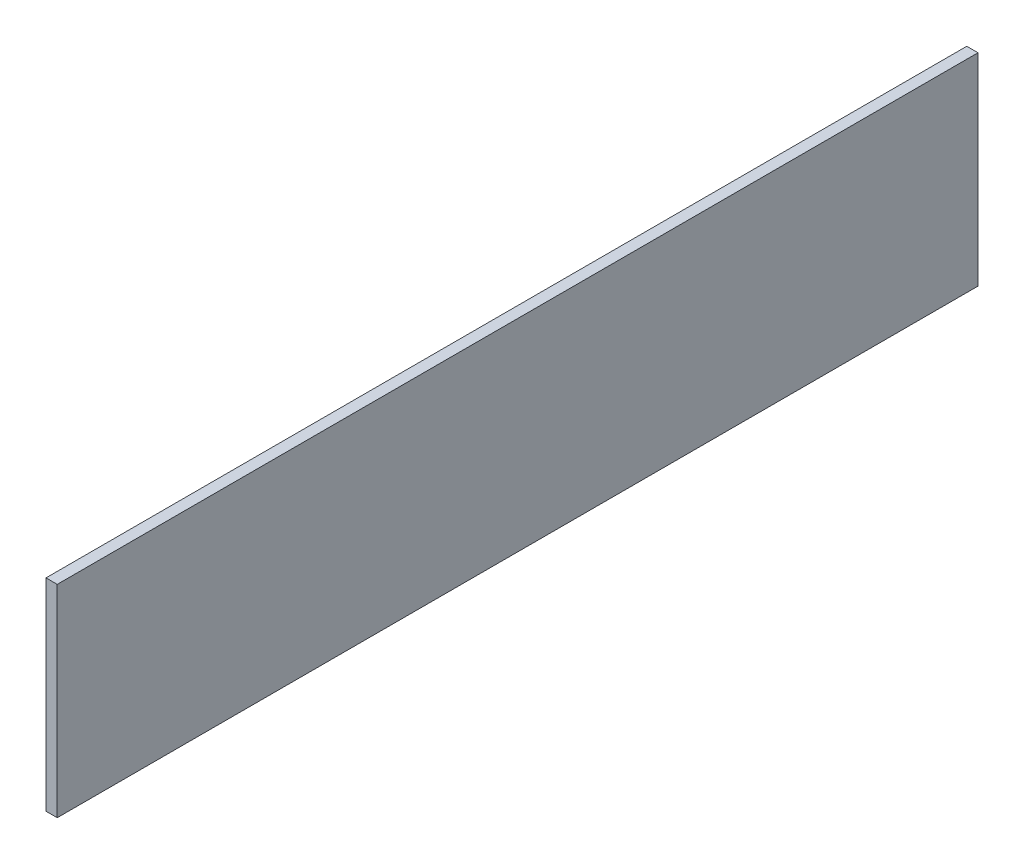
SolidWorks part; units mm, degrees
ref_plane "Front Plane" through (0, 0, 0) normal (0, 0, 1) x (1, 0, 0)
ref_plane "Top Plane" through (0, 0, 0) normal (0, 1, 0) x (1, 0, 0)
ref_plane "Right Plane" through (0, 0, 0) normal (1, 0, 0) x (0, 0, -1)
sketch "Sketch1" plane through (0, 0, 0) normal (1, 0, 0) x (0, 0, -1)
  line L1 (-130.175, 0) -> (130.175, 0)
  line L2 (-130.175, 0) -> (-130.175, 57.15)
  line L3 (-130.175, 57.15) -> (130.175, 57.15)
  line L4 (130.175, 0) -> (130.175, 57.15)
  line L5 (-130.175, 0) -> (130.175, 57.15) construction
  line L6 (-130.175, 57.15) -> (130.175, 0) construction
  point P4 (0, 28.575)
  dimension "D1" = 260.35
  dimension "D2" = 57.15
extrude "Boss-Extrude1" add sketch "Sketch1" along normal blind 3.175
